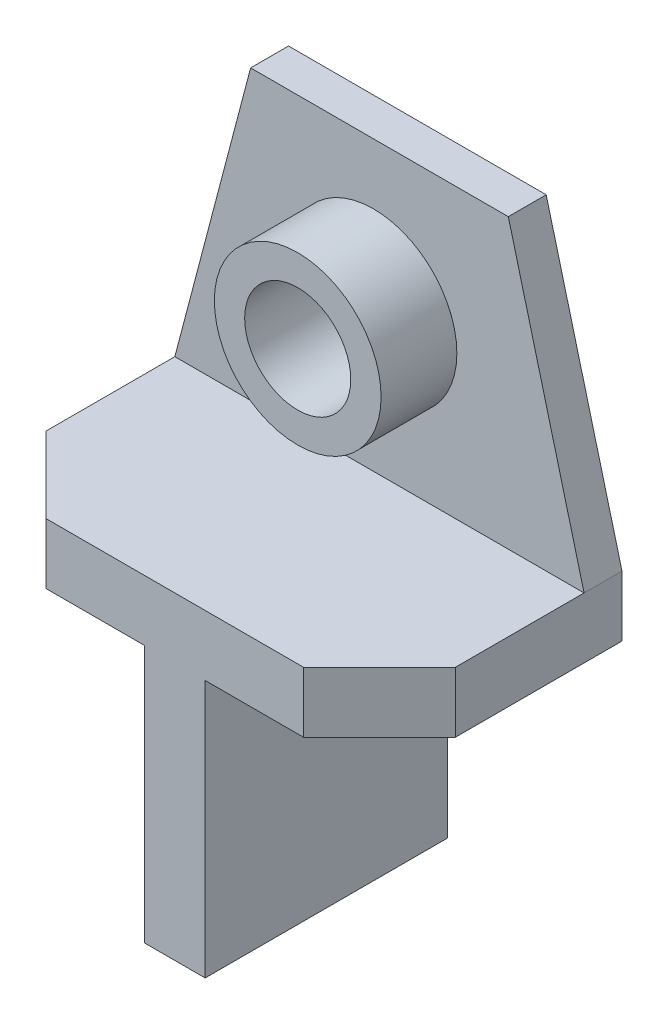
SolidWorks part; units mm, degrees
ref_plane "Front Plane" through (0, 0, 0) normal (0, 0, 1) x (1, 0, 0)
ref_plane "Top Plane" through (0, 0, 0) normal (0, 1, 0) x (1, 0, 0)
ref_plane "Right Plane" through (0, 0, 0) normal (1, 0, 0) x (0, 0, -1)
sketch "Sketch2" plane through (0, 0, 0) normal (0, 0, 1) x (1, 0, 0)
  line L0 (0.7885, -32.9382) -> (0.7885, 27.4917) construction
  line L1 (4.7885, -32.9382) -> (-3.2115, -32.9382)
  line L2 (4.7885, -32.9382) -> (4.7885, 1.0618)
  line L4 (-3.2115, -32.9382) -> (-3.2115, 1.0618)
  line L7 (-26.2115, 9.0618) -> (27.7885, 9.0618)
  line L8 (-26.2115, 9.0618) -> (-26.2115, 1.0618)
  line L9 (-26.2115, 1.0618) -> (-3.2115, 1.0618)
  line L10 (27.7885, 9.0618) -> (27.7885, 1.0618)
  line L11 (3.9601, 33.7623) -> (4, 33.7588) construction
  line L16 (4.7885, 1.0618) -> (27.7885, 1.0618)
  point P0 (0, 0)
  point P6 (0, 34.1023)
  point P14 (0.7885, 9.0618)
  dimension "D1" = 8
  dimension "D2" = 8
  dimension "D3" = 34
  dimension "D4" = 54
extrude "Boss-Extrude1" add sketch "Sketch2" along normal blind 32
chamfer "Chamfer3" distance 10 angle 45 1 edges at (27.7885, 5.0618, 32)
chamfer "Chamfer4" distance 10 angle 45 1 edges at (-26.2115, 5.0618, 32)
sketch "Sketch5" plane through (0, 0, 0) normal (0, 0, 1) x (1, 0, 0)
  line L0 (27.7885, 9.0618) -> (17.7885, 47.0618)
  line L1 (17.7885, 47.0618) -> (-16.2115, 47.0618)
  line L2 (-16.2115, 47.0618) -> (-26.2115, 9.0618)
  line L3 (-26.2115, 9.0618) -> (27.7885, 9.0618)
  line L4 (0.7885, 9.0618) -> (0.7885, 71.9566) construction
  point P8 (0.7885, 47.0618)
  dimension "D1" = 34
  dimension "D2" = 38
extrude "Boss-Extrude3" add sketch "Sketch5" along normal blind 5
sketch "Sketch6" plane through (0, 0, 5) normal (0, 0, 1) x (1, 0, 0)
  circle A0 centre (0, 28.0618) radius 7
  circle A1 centre (0, 28.0618) radius 11
  dimension "D1" = 22
  dimension "D2" = 14
extrude "Boss-Extrude4" add sketch "Sketch6" along normal blind 10
sketch "Sketch7" plane through (0, 0, 5) normal (0, 0, 1) x (1, 0, 0)
  circle A1 centre (0, 28.0618) radius 7
  circle A2 centre (0, 28.0618) radius 7
  dimension "D1" = 0
extrude "Cut-Extrude1" cut sketch "Sketch7" against normal blind 10
